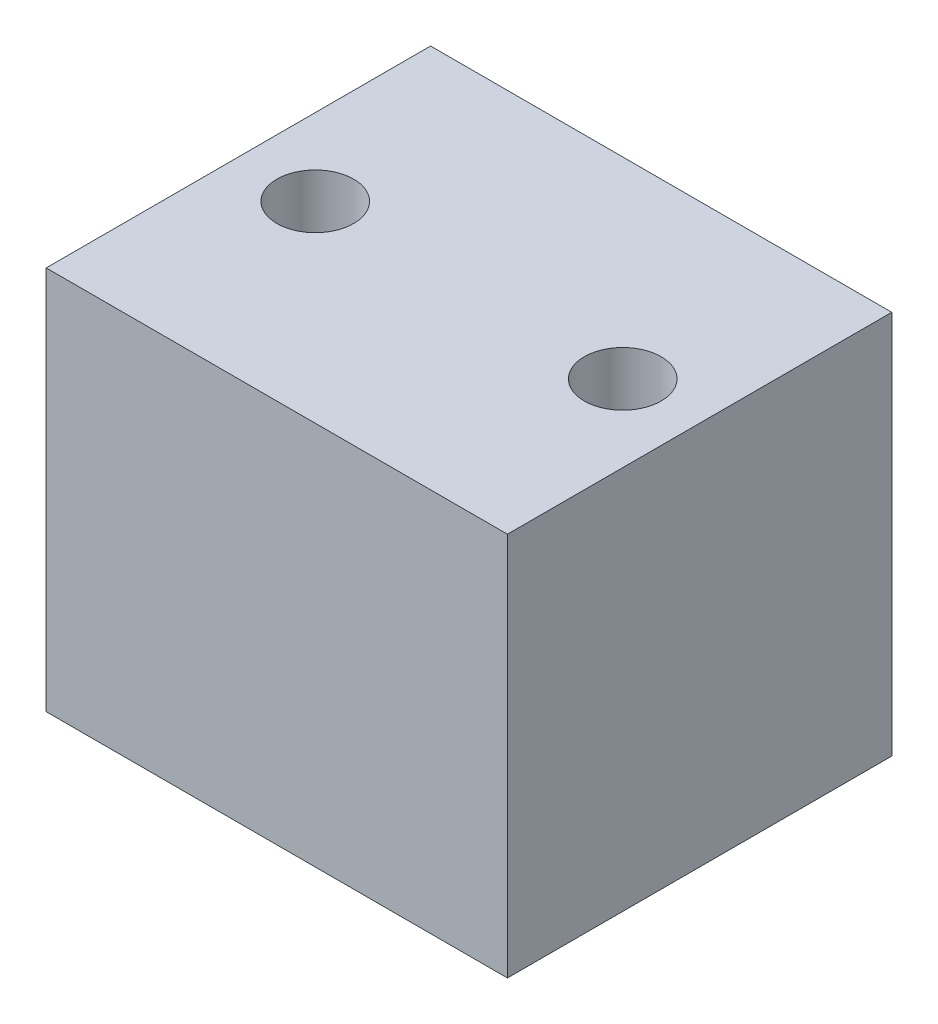
SolidWorks part; units mm, degrees
ref_plane "Front Plane" through (0, 0, 0) normal (0, 0, 1) x (1, 0, 0)
ref_plane "Top Plane" through (0, 0, 0) normal (0, 1, 0) x (1, 0, 0)
ref_plane "Right Plane" through (0, 0, 0) normal (1, 0, 0) x (0, 0, -1)
sketch "Sketch1" plane through (0, 0, 0) normal (0, 1, 0) x (1, 0, 0)
  line L0 (-12.5, -2.5) -> (-12.5, 2.5) construction
  line L1 (-15, 14.5) -> (15, 14.5) construction
  line L2 (-15, 14.5) -> (-15, -7.5) construction
  line L3 (-15, -7.5) -> (15, -7.5) construction
  line L4 (15, 14.5) -> (15, -7.5) construction
  line L5 (-7.5, -2.5) -> (-7.5, 2.5) construction
  line L6 (7.5, -2.5) -> (7.5, 2.5) construction
  line L7 (12.5, -2.5) -> (12.5, 2.5) construction
  line L8 (-10, 5) -> (-10, 2.5) construction
  line L9 (-10, 2.5) -> (-10, -2.5) construction
  line L10 (-10, -2.5) -> (-10, -5) construction
  line L11 (-10, 0) -> (-7.5, 0) construction
  line L12 (-7.5, 0) -> (0, 0) construction
  line L13 (0, 0) -> (7.5, 0) construction
  line L14 (-10, 2.5) -> (10, 2.5) construction
  line L15 (-15, 7.5) -> (15, 7.5) construction
  line L16 (-10, -2.5) -> (10, -2.5) construction
  line L17 (0, 0) -> (0, -7.5) construction
  line L18 (0, 0) -> (0, 7.5) construction
  line L19 (-15, 12.5) -> (15, 12.5)
  line L20 (-15, 19.5) -> (15, 19.5)
  line L21 (-15, 19.5) -> (-15, -12.5)
  line L22 (-15, -12.5) -> (15, -12.5)
  line L23 (15, 19.5) -> (15, -12.5)
  line L24 (0, -12.5) -> (0, 0) construction
  line L25 (0, 0) -> (0, 12.5) construction
  circle A0 centre (-10, 2.5) radius 2.5 construction
  circle A1 centre (-10, -2.5) radius 2.5 construction
  circle A2 centre (10, 2.5) radius 2.5 construction
  circle A3 centre (10, -2.5) radius 2.5 construction
  circle A4 centre (-10, 0) radius 2.5
  circle A5 centre (10, 0) radius 2.5
  dimension "D1" = 22
  dimension "D2" = 30
  dimension "D3" = 7
  dimension "D4" = 15
  dimension "D5" = 5
  dimension "D6" = 10
  dimension "D7" = 5
  dimension "D8" = 5
extrude "Boss-Extrude1" add sketch "Sketch1" along normal blind 25 contours L4 L1 L2 L3 A3 L6 A2 L7 A1 L0 A0 L5 | L23 L20 L21 L22 A5 A4
